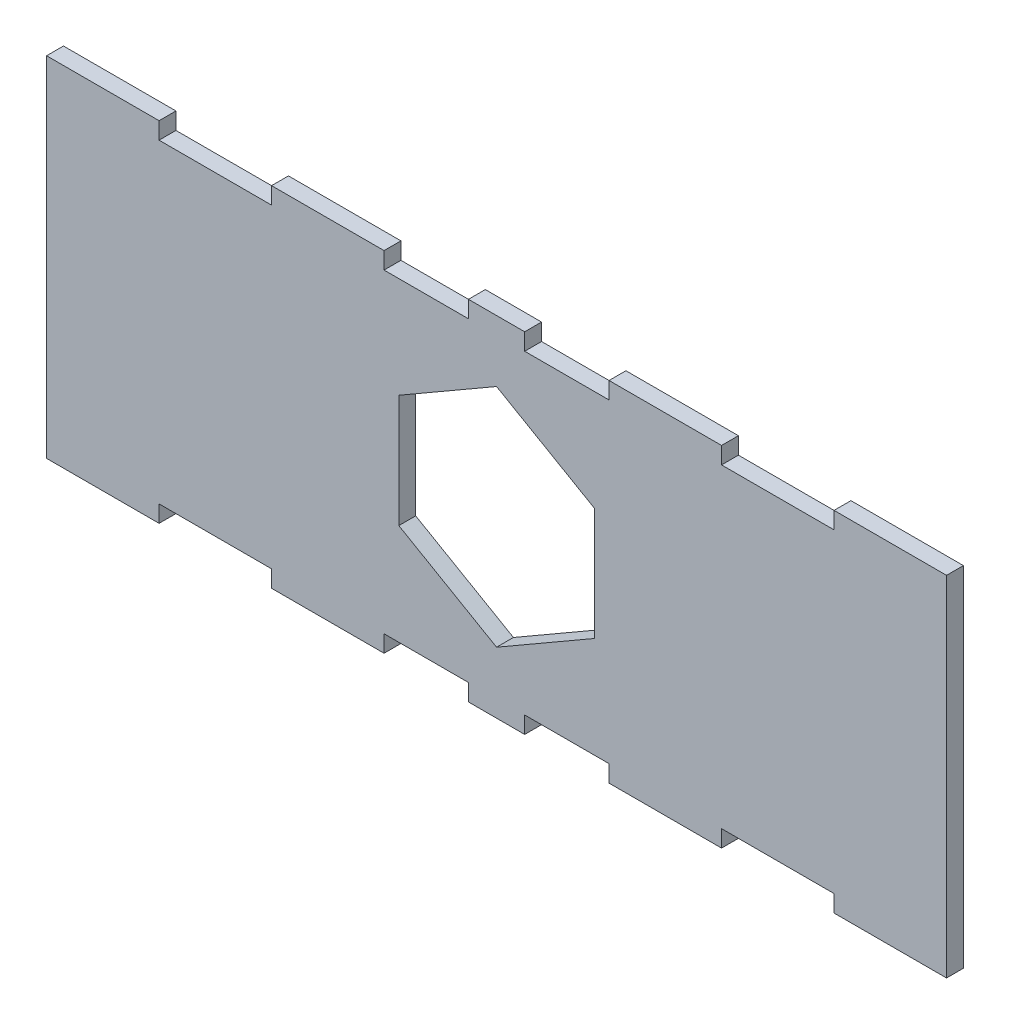
SolidWorks part; units mm, degrees
ref_plane "Přední rovina" through (0, 0, 0) normal (0, 0, 1) x (1, 0, 0)
ref_plane "Horní rovina" through (0, 0, 0) normal (0, 1, 0) x (1, 0, 0)
ref_plane "Pravá rovina" through (0, 0, 0) normal (1, 0, 0) x (0, 0, -1)
sketch "Skica1" plane through (0, 0, 0) normal (0, 0, 1) x (1, 0, 0)
  line L0 (20, 3) -> (23.5, 3)
  line L1 (0, 0) -> (20, 0)
  line L2 (0, 0) -> (0, 62)
  line L5 (20, 3) -> (20, 0)
  line L6 (40, 3) -> (40, 0)
  line L7 (60, 3) -> (60, 0)
  line L8 (75, 3) -> (75, 0)
  line L9 (40, 0) -> (60, 0)
  line L10 (75, 0) -> (85, 0)
  line L11 (60, 3) -> (75, 3)
  line L12 (212.6239, 31) -> (-52.6239, 31) construction
  line L13 (60, 59) -> (75, 59)
  line L14 (75, 59) -> (75, 62)
  line L15 (75, 62) -> (85, 62)
  line L16 (0, 62) -> (20, 62)
  line L17 (20, 59) -> (20, 62)
  line L18 (20, 59) -> (40, 59)
  line L19 (40, 59) -> (40, 62)
  line L20 (40, 62) -> (60, 62)
  line L21 (60, 59) -> (60, 62)
  line L22 (23.5, 3) -> (40, 3)
  line L37 (80, 51.0679) -> (62.6207, 41.0339)
  line L38 (62.6207, 41.0339) -> (62.6207, 20.9661)
  line L39 (62.6207, 20.9661) -> (80, 10.9321)
  line L40 (88.6896, 46.0509) -> (80, 51.0679) [skipped]
  line L41 (97.3793, 20.9661) -> (97.3793, 31) [skipped]
  line L42 (80, 10.9321) -> (88.6896, 15.9491) [skipped]
  line L43 (80, 0) -> (80, 82.1995) construction
  line L44 (97.3793, 20.9661) -> (80, 10.9321)
  line L45 (97.3793, 41.0339) -> (97.3793, 20.9661)
  line L46 (80, 51.0679) -> (97.3793, 41.0339)
  line L47 (136.5, 3) -> (120, 3)
  line L48 (100, 59) -> (100, 62)
  line L49 (120, 62) -> (100, 62)
  line L50 (120, 59) -> (120, 62)
  line L51 (140, 59) -> (120, 59)
  line L52 (140, 59) -> (140, 62)
  line L53 (160, 62) -> (140, 62)
  line L54 (85, 59) -> (85, 62)
  line L55 (100, 59) -> (85, 59)
  line L56 (100, 3) -> (85, 3)
  line L57 (120, 0) -> (100, 0)
  line L58 (85, 3) -> (85, 0)
  line L59 (100, 3) -> (100, 0)
  line L60 (120, 3) -> (120, 0)
  line L61 (140, 3) -> (140, 0)
  line L62 (160, 0) -> (160, 62)
  line L63 (160, 0) -> (140, 0)
  line L64 (140, 3) -> (136.5, 3)
  circle A0 centre (80, 31) radius 17.3793 construction
  dimension "D1" = 31
  dimension "D2" = 62
  dimension "D3" = 3
  dimension "D4" = 20
  dimension "D5" = 20
  dimension "D6" = 20
  dimension "D7" = 15
  dimension "D9" = 62
  dimension "D10" = 59
  dimension "D11" = 56
  dimension "D12" = 20
  dimension "D13" = 15
  dimension "D15" = 20
  dimension "D16" = 90
extrude "Přidat vysunutím1" add sketch "Skica1" along normal blind 3
